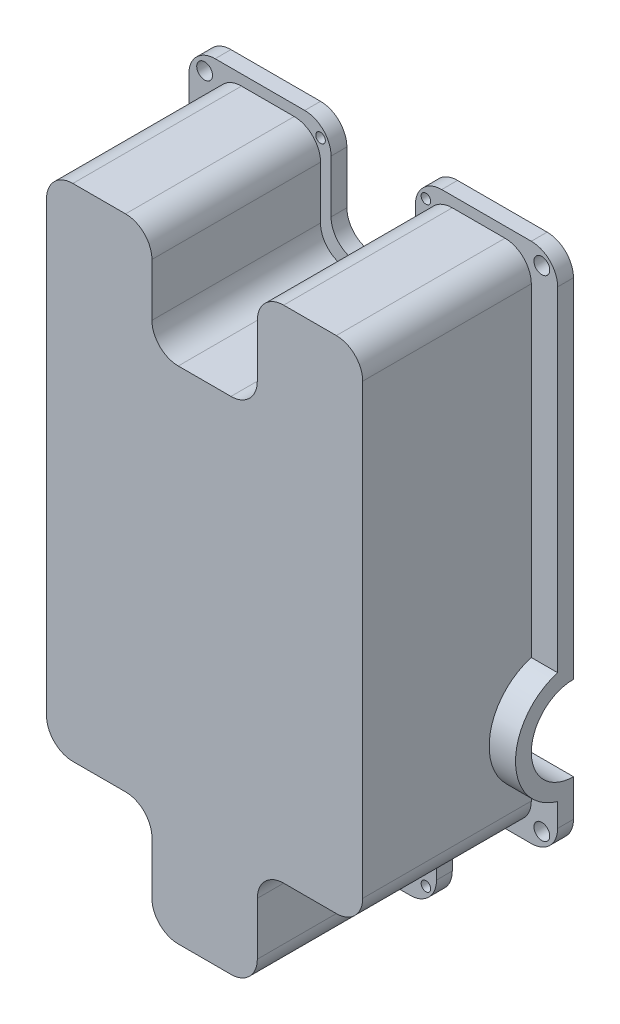
SolidWorks part; units mm, degrees
ref_plane "Front Plane" through (0, 0, 0) normal (0, 0, 1) x (1, 0, 0)
ref_plane "Top Plane" through (0, 0, 0) normal (0, 1, 0) x (1, 0, 0)
ref_plane "Right Plane" through (0, 0, 0) normal (1, 0, 0) x (0, 0, -1)
sketch "Sketch1" plane through (0, 0, 0) normal (0, 0, 1) x (1, 0, 0)
  line L1 (-35, -59.5) -> (35, -59.5)
  line L2 (-35, -59.5) -> (-35, 59.5)
  line L3 (-35, 59.5) -> (35, 59.5)
  line L4 (35, -59.5) -> (35, 59.5)
  line L5 (-35, -59.5) -> (35, 59.5) construction
  line L6 (-35, 59.5) -> (35, -59.5) construction
  point P0 (0, 0)
  dimension "D1" = 119
  dimension "D2" = 70
extrude "Boss-Extrude1" add sketch "Sketch1" along normal blind 35
sketch "Sketch2" plane through (35, 0, 0) normal (1, 0, 0) x (0, 0, -1)
  line L0 (0, -59.5) -> (0, 59.5) construction
  line L1 (-35, -59.5) -> (0, -59.5) construction
  circle A0 centre (0, -19.5) radius 8
  dimension "D2" = 16
  dimension "D1" = 40
extrude "Cut-Extrude1" cut sketch "Sketch2" against normal blind 8
sketch "Sketch3" plane through (0, 0, 0) normal (0, 0, -1) x (-1, 0, 0)
  line L0 (-35, -11.5) -> (-35, 59.5) construction
  line L1 (-27, 54.5) -> (-13, 54.5)
  line L2 (-27, 54.5) -> (-27, -34.5)
  line L3 (-27, -34.5) -> (-13, -34.5)
  line L4 (-13, 54.5) -> (-13, 27)
  line L5 (-7, 34.5) -> (7, 34.5)
  line L6 (-7, 34.5) -> (-7, 27)
  line L7 (-7, -54.5) -> (7, -54.5)
  line L8 (7, 34.5) -> (7, -12)
  line L9 (13, 54.5) -> (27, 54.5)
  line L10 (13, 54.5) -> (13, -12)
  line L11 (13, -34.5) -> (27, -34.5)
  line L12 (27, 54.5) -> (27, -34.5)
  line L13 (-35, -19.5) -> (35, -19.5) construction
  line L14 (-35, -11.5) -> (-35, -27.5) construction
  line L15 (35, 59.5) -> (35, -59.5) construction
  line L16 (-35, 19.5) -> (35, 19.5) construction
  line L17 (-13, 27) -> (-7, 27)
  line L18 (-13, 12) -> (-7, 12)
  line L19 (-13, 12) -> (-13, -34.5)
  line L20 (-7, 12) -> (-7, -54.5)
  line L21 (7, -27) -> (13, -27)
  line L22 (7, -12) -> (13, -12)
  line L23 (7, -27) -> (7, -54.5)
  line L24 (13, -27) -> (13, -34.5)
  point P22 (0, 19.5)
  dimension "D1" = 8
  dimension "D2" = 14
  dimension "D3" = 6
  dimension "D4" = 6
  dimension "D5" = 15
  dimension "D6" = 39
  dimension "D7" = 89
  dimension "D8" = 15
  dimension "D9" = 7.5
  dimension "D10" = 15
  dimension "D11" = 7.5
  dimension "D12" = 15
  dimension "D13" = 89
extrude "Cut-Extrude2" cut sketch "Sketch3" against normal blind 32
sketch "Sketch4" plane through (-35, 0, 0) normal (-1, 0, 0) x (0, 0, 1)
  line L0 (0, 59.5) -> (0, -59.5) construction
  line L1 (35, -59.5) -> (0, -59.5) construction
  circle A0 centre (0, 19.5) radius 7.5
  dimension "D1" = 15
  dimension "D2" = 79
extrude "Cut-Extrude3" cut sketch "Sketch4" against normal blind 8
sketch "Sketch5" plane through (0, 0, 0) normal (0, 0, -1) x (-1, 0, 0)
  line L0 (-35, 59.5) -> (35, 59.5) construction
  line L1 (-8, 59.5) -> (8, 59.5)
  line L2 (-8, 59.5) -> (-8, 39.5)
  line L3 (-8, 39.5) -> (8, 39.5)
  line L4 (8, 59.5) -> (8, 39.5)
  line L5 (-35, -59.5) -> (-35, -27.5) construction
  line L6 (-35, -39.5) -> (-12, -39.5)
  line L7 (-35, -39.5) -> (-35, -59.5)
  line L8 (-35, -59.5) -> (-12, -59.5)
  line L9 (-12, -39.5) -> (-12, -59.5)
  line L10 (35, -59.5) -> (-35, -59.5) construction
  line L11 (35, 12) -> (35, -59.5) construction
  line L12 (35, -39.5) -> (12, -39.5)
  line L13 (35, -39.5) -> (35, -59.5)
  line L14 (35, -59.5) -> (12, -59.5)
  line L15 (12, -39.5) -> (12, -59.5)
  line L16 (-7, 12) -> (-7, -54.5) construction
  line L17 (-27, -34.5) -> (-13, -34.5) construction
  line L18 (7, -54.5) -> (7, -27) construction
  line L19 (13, -34.5) -> (27, -34.5) construction
  line L20 (-13, 27) -> (-13, 54.5) construction
  line L21 (13, 54.5) -> (13, -12) construction
  line L22 (7, 34.5) -> (-7, 34.5) construction
  dimension "D1" = 5
  dimension "D2" = 5
  dimension "D3" = 5
  dimension "D4" = 5
  dimension "D5" = 5
  dimension "D6" = 5
  dimension "D7" = 5
extrude "Cut-Extrude4" cut sketch "Sketch5" against normal through all
sketch "Sketch6" plane through (35, 0, 0) normal (1, 0, 0) x (0, 0, -1)
  line L2 (-3, 59.5) -> (-35, 59.5)
  line L3 (-3, -39.5) -> (-35, -39.5)
  line L4 (-3, -39.5) -> (-3, -30.083)
  line L5 (-3, -8.917) -> (-3, 59.5)
  line L6 (-3, -39.5) -> (-3, -30.083)
  line L7 (-3, -8.917) -> (-3, 59.5)
  line L8 (-35, -39.5) -> (-35, 59.5)
  arc A2 (-3, -8.917) -> (-3, -30.083) centre (0, -19.5) ccw
  arc A3 (-3, -8.917) -> (-3, -30.083) centre (0, -19.5) ccw
  dimension "D1" = 3
extrude "Cut-Extrude5" cut sketch "Sketch6" against normal blind 5
sketch "Sketch7" plane through (0, -39.5, 0) normal (0, -1, 0) x (1, 0, 0)
  line L1 (12, 35) -> (30, 35)
  line L2 (12, 35) -> (12, 3)
  line L3 (12, 3) -> (30, 3)
  line L4 (30, 35) -> (30, 3)
extrude "Cut-Extrude6" cut sketch "Sketch7" against normal blind 2
sketch "Sketch8" plane through (12, 0, 0) normal (1, 0, 0) x (0, 0, -1)
  line L1 (-3, -37.5) -> (-35, -37.5)
  line L2 (-3, -37.5) -> (-3, -59.5)
  line L3 (-3, -59.5) -> (-35, -59.5)
  line L4 (-35, -37.5) -> (-35, -59.5)
extrude "Cut-Extrude7" cut sketch "Sketch8" against normal blind 2
sketch "Sketch9" plane through (0, -59.5, 0) normal (0, -1, 0) x (1, 0, 0)
  line L1 (10, 3) -> (-12, 3)
  line L2 (10, 3) -> (10, 35)
  line L3 (10, 35) -> (-12, 35)
  line L4 (-12, 3) -> (-12, 35)
extrude "Cut-Extrude8" cut sketch "Sketch9" against normal blind 2
sketch "Sketch10" plane through (-12, 0, 0) normal (-1, 0, 0) x (0, 0, 1)
  line L1 (3, -57.5) -> (35, -57.5)
  line L2 (3, -57.5) -> (3, -39.5)
  line L3 (3, -39.5) -> (35, -39.5)
  line L4 (35, -57.5) -> (35, -39.5)
extrude "Cut-Extrude9" cut sketch "Sketch10" against normal blind 2
sketch "Sketch11" plane through (0, -39.5, 0) normal (0, -1, 0) x (1, 0, 0)
  line L1 (-10, 3) -> (-35, 3)
  line L2 (-10, 3) -> (-10, 35)
  line L3 (-10, 35) -> (-35, 35)
  line L4 (-35, 3) -> (-35, 35)
extrude "Cut-Extrude10" cut sketch "Sketch11" against normal blind 2
sketch "Sketch12" plane through (-35, 0, 0) normal (-1, 0, 0) x (0, 0, 1)
  line L2 (3, 59.5) -> (35, 59.5)
  line L3 (35, 59.5) -> (35, -37.5)
  line L4 (3, 59.5) -> (3, 29.5623)
  line L5 (3, 9.4377) -> (3, -39.5)
  line L6 (3, 59.5) -> (3, 29.5623)
  line L7 (3, 9.4377) -> (3, -37.5)
  line L8 (35, -37.5) -> (3, -37.5)
  arc A2 (3, 9.4377) -> (3, 29.5623) centre (0, 19.5) ccw
  arc A3 (3, 9.4377) -> (3, 29.5623) centre (0, 19.5) ccw
  dimension "D1" = 3
extrude "Cut-Extrude11" cut sketch "Sketch12" against normal blind 5
sketch "Sketch13" plane through (0, 59.5, 0) normal (0, 1, 0) x (1, 0, 0)
  line L1 (-30, -3) -> (-8, -3)
  line L2 (-30, -3) -> (-30, -35)
  line L3 (-30, -35) -> (-8, -35)
  line L4 (-8, -3) -> (-8, -35)
extrude "Cut-Extrude12" cut sketch "Sketch13" against normal blind 2
sketch "Sketch14" plane through (-8, 0, 0) normal (1, 0, 0) x (0, 0, -1)
  line L1 (-3, 57.5) -> (-35, 57.5)
  line L2 (-3, 57.5) -> (-3, 39.5)
  line L3 (-3, 39.5) -> (-35, 39.5)
  line L4 (-35, 57.5) -> (-35, 39.5)
extrude "Cut-Extrude13" cut sketch "Sketch14" against normal blind 2
sketch "Sketch15" plane through (0, 39.5, 0) normal (0, 1, 0) x (1, 0, 0)
  line L1 (-10, -3) -> (8, -3)
  line L2 (-10, -3) -> (-10, -35)
  line L3 (-10, -35) -> (8, -35)
  line L4 (8, -3) -> (8, -35)
extrude "Cut-Extrude14" cut sketch "Sketch15" against normal blind 2
sketch "Sketch16" plane through (8, 0, 0) normal (-1, 0, 0) x (0, 0, 1)
  line L1 (3, 37.5) -> (35, 37.5)
  line L2 (3, 37.5) -> (3, 59.5)
  line L3 (3, 59.5) -> (35, 59.5)
  line L4 (35, 37.5) -> (35, 59.5)
extrude "Cut-Extrude15" cut sketch "Sketch16" against normal blind 2
sketch "Sketch17" plane through (0, 59.5, 0) normal (0, 1, 0) x (1, 0, 0)
  line L1 (10, -3) -> (30, -3)
  line L2 (10, -3) -> (10, -35)
  line L3 (10, -35) -> (30, -35)
  line L4 (30, -3) -> (30, -35)
extrude "Cut-Extrude16" cut sketch "Sketch17" against normal blind 2
fillet "Fillet1" radius 5 12 edges at (-13, -34.5, 16) (27, -34.5, 16) (7, -54.5, 16) (7, 34.5, 16) (-7, 34.5, 16) (13, -34.5, 16) (-7, -54.5, 16) (-27, -34.5, 16) (27, 54.5, 16) (-13, 54.5, 16) (13, 54.5, 16) (-27, 54.5, 16)
fillet "Fillet2" radius 5 12 edges at (-30, 57.5, 19) (30, 57.5, 19) (30, -37.5, 19) (10, -37.5, 19) (10, -57.5, 19) (-10, -57.5, 19) (-10, -37.5, 19) (-30, -37.5, 19) (-10, 37.5, 19) (10, 37.5, 19) (10, 57.5, 19) (-10, 57.5, 19)
fillet "Fillet3" radius 5 12 edges at (35, -39.5, 1.5) (12, -39.5, 1.5) (12, -59.5, 1.5) (-12, -39.5, 1.5) (-12, -59.5, 1.5) (-35, -39.5, 1.5) (-8, 39.5, 1.5) (35, 59.5, 1.5) (8, 59.5, 1.5) (8, 39.5, 1.5) (-8, 59.5, 1.5) (-35, 59.5, 1.5)
sketch "Sketch18" plane through (0, 0, 0) normal (0, 0, -1) x (-1, 0, 0)
  line L0 (-35, -11.5) -> (-35, 54.5) construction
  line L1 (32, 56.5) -> (-32, 56.5) construction
  line L2 (32, 56.5) -> (32, -36.5) construction
  line L3 (32, -36.5) -> (-32, -36.5) construction
  line L4 (-32, 56.5) -> (-32, -36.5) construction
  line L5 (-30, 59.5) -> (-13, 59.5) construction
  line L6 (-7, 12) -> (-7, -49.5) construction
  line L7 (7, -49.5) -> (7, -27) construction
  circle A0 centre (-32, 56.5) radius 1.5
  circle A1 centre (32, 56.5) radius 1.5
  circle A2 centre (-32, -36.5) radius 1.5
  circle A3 centre (32, -36.5) radius 1.5
  circle A4 centre (10, -36.5) radius 1.5
  circle A5 centre (-10, -36.5) radius 1.5
  dimension "D7" = 3
  dimension "D1" = 64
  dimension "D2" = 93
  dimension "D3" = 3
  dimension "D4" = 3
  dimension "D5" = 3
  dimension "D6" = 3
extrude "Cut-Extrude17" cut sketch "Sketch18" against normal blind 10
sketch "Sketch19" plane through (0, 0, 0) normal (0, 0, -1) x (-1, 0, 0)
  line L0 (-8, 54.5) -> (-8, 44.5) construction
  line L1 (-10, 56.5) -> (10, 56.5) construction
  line L2 (-10, 56.5) -> (-10, -56.5) construction
  line L3 (-10, -56.5) -> (10, -56.5) construction
  line L4 (10, 56.5) -> (10, -56.5) construction
  line L5 (-30, 59.5) -> (-13, 59.5) construction
  circle A0 centre (-10, 56.5) radius 0.91
  circle A1 centre (10, 56.5) radius 0.91
  circle A2 centre (10, -56.5) radius 0.91
  circle A3 centre (-10, -56.5) radius 0.91
  dimension "D5" = 1.82
  dimension "D1" = 113
  dimension "D2" = 20
  dimension "D3" = 2
  dimension "D4" = 3
extrude "Cut-Extrude18" cut sketch "Sketch19" against normal blind 10
sketch "Sketch20" plane through (13, 0, 0) normal (1, 0, 0) x (0, 0, -1)
  line L0 (0, 27) -> (-32, 27)
  line L1 (-32, 27) -> (-32, 12)
  line L2 (-32, 12) -> (0, 12)
  arc A0 (0, 27) -> (0, 12) centre (0, 19.5) ccw
  point P1 (0, 0)
  point P6 (0, 19.5)
  point P8 (0, 19.5)
  point P9 (0, 34.5)
  point P10 (0, 27)
  dimension "D1" = 15
  dimension "D2" = 32
extrude "Boss-Extrude2" add sketch "Sketch20" against normal blind 6
sketch "Sketch21" plane through (-7, 0, 0) normal (1, 0, 0) x (0, 0, -1)
  line L0 (0, -12) -> (-32, -12)
  line L1 (-32, -12) -> (-32, -27)
  line L2 (-32, -27) -> (0, -27)
  arc A0 (0, -12) -> (0, -27) centre (0, -19.5) ccw
  dimension "D1" = 15
  dimension "D2" = 32
extrude "Boss-Extrude3" add sketch "Sketch21" against normal blind 6
